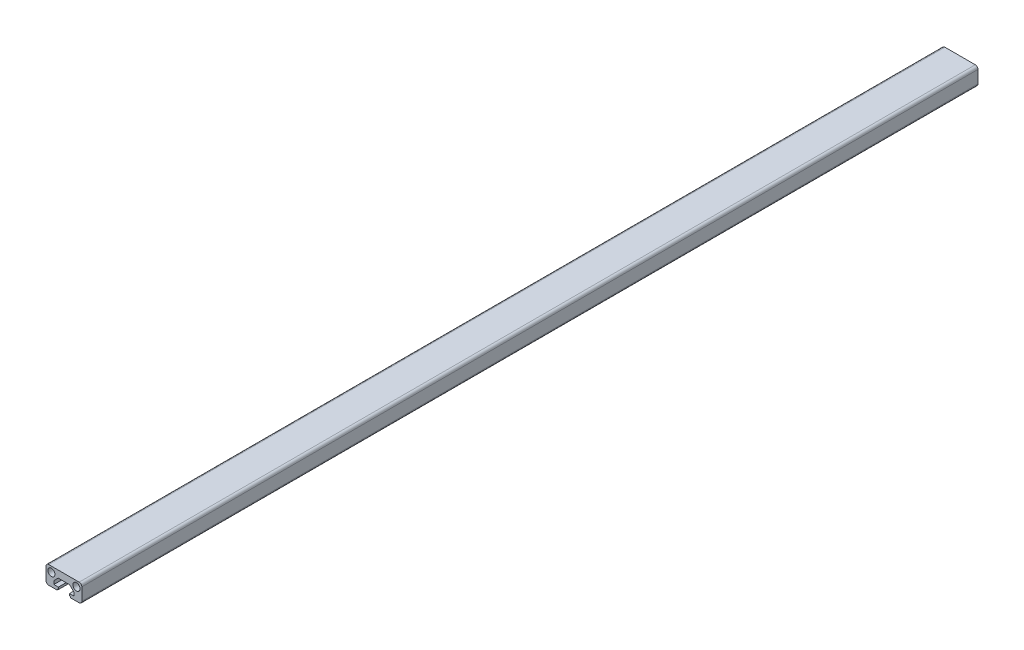
SolidWorks part; units mm, degrees
ref_plane "前视基准面" through (0, 0, 0) normal (0, 0, 1) x (1, 0, 0)
ref_plane "上视基准面" through (0, 0, 0) normal (0, 1, 0) x (1, 0, 0)
ref_plane "右视基准面" through (0, 0, 0) normal (1, 0, 0) x (0, 0, -1)
sketch "草图1" plane through (0, 0, 0) normal (0, 0, 1) x (1, 0, 0)
  line L0 (-8.5, 0) -> (-3.95, 0)
  line L1 (-3.65, 0.3) -> (-3.65, 0.6)
  line L2 (-3.65, 0.6) -> (-3.1, 0.6)
  line L3 (-3.1, 0.6) -> (-3.1, 1.8)
  line L4 (-3.1, 1.8) -> (-5.6, 1.8)
  line L5 (-5.6, 1.8) -> (-5.6, 3.6929)
  line L6 (-5.6, 3.6929) -> (-3.1929, 6.1)
  line L7 (-3.1929, 6.1) -> (3.1929, 6.1)
  line L8 (0, 6.1) -> (0, 10) construction
  line L9 (8.5, 10) -> (-8.5, 10)
  line L10 (-10, 8.5) -> (-10, 1.5)
  line L11 (0, 6.1) -> (0, 0) construction
  line L12 (0, 10) -> (-10, 0) construction
  line L13 (5.6, 3.6929) -> (3.1929, 6.1)
  line L14 (5.6, 1.8) -> (5.6, 3.6929)
  line L15 (3.1, 1.8) -> (5.6, 1.8)
  line L16 (3.1, 0.6) -> (3.1, 1.8)
  line L17 (3.65, 0.6) -> (3.1, 0.6)
  line L18 (3.65, 0.3) -> (3.65, 0.6)
  line L19 (8.5, 0) -> (3.95, 0)
  line L20 (10, 8.5) -> (10, 1.5)
  circle A0 centre (-7, 7) radius 2
  arc A1 (-8.5, 0) -> (-10, 1.5) centre (-8.5, 1.5) cw
  arc A2 (-8.5, 10) -> (-10, 8.5) centre (-8.5, 8.5) ccw
  arc A3 (8.5, 0) -> (10, 1.5) centre (8.5, 1.5) ccw
  arc A4 (8.5, 10) -> (10, 8.5) centre (8.5, 8.5) cw
  circle A5 centre (7, 7) radius 2
  arc A6 (3.65, 0.3) -> (3.95, 0) centre (3.95, 0.3) ccw
  arc A7 (-3.95, 0) -> (-3.65, 0.3) centre (-3.95, 0.3) ccw
  point P37 (3.65, 0)
  point P40 (-3.65, 0)
  dimension "D10" = 14
  dimension "D11" = 3
  dimension "D12" = 4
  dimension "D14" = 1.5
  dimension "D15" = 0.3
  dimension "D1" = 20
  dimension "D2" = 1.2
  dimension "D3" = 1.8
  dimension "D4" = 10
  dimension "D5" = 6.2
  dimension "D6" = 7.3
  dimension "D7" = 3.9
  dimension "D8" = 11.2
  dimension "D9" = 45
  dimension "D13" = 0.5
extrude "凸台-拉伸1" add sketch "草图1" along normal mid plane 500
